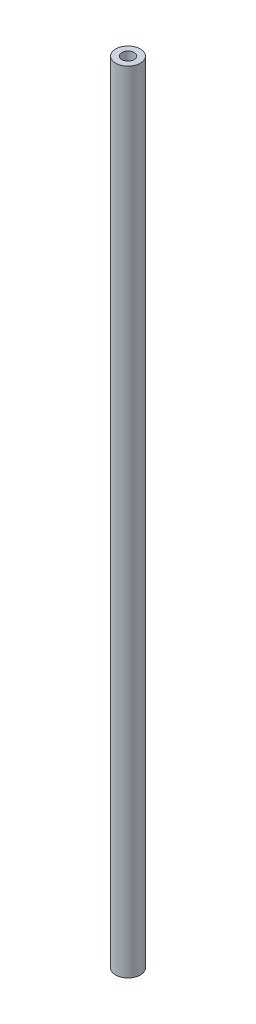
SolidWorks part; units mm, degrees
ref_plane "Front Plane" through (0, 0, 0) normal (0, 0, 1) x (1, 0, 0)
ref_plane "Top Plane" through (0, 0, 0) normal (0, 1, 0) x (1, 0, 0)
ref_plane "Right Plane" through (0, 0, 0) normal (1, 0, 0) x (0, 0, -1)
sketch "Sketch1" plane through (0, 0, 0) normal (0, 1, 0) x (1, 0, 0)
  circle A0 centre (0, 0) radius 3.175
  circle A1 centre (0, 0) radius 1.5875
  dimension "D1" = 6.35
  dimension "D2" = 3.175
extrude "Boss-Extrude1" add sketch "Sketch1" along normal blind 203.2
